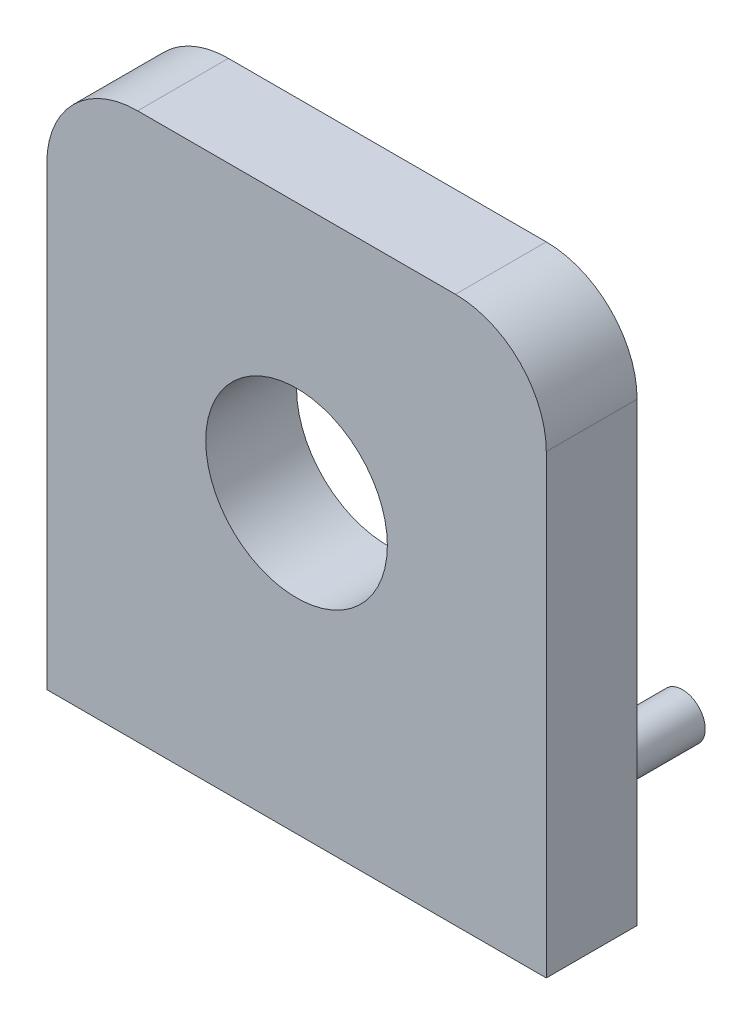
SolidWorks part; units mm, degrees
ref_plane "Front Plane" through (0, 0, 0) normal (0, 0, 1) x (1, 0, 0)
ref_plane "Top Plane" through (0, 0, 0) normal (0, 1, 0) x (1, 0, 0)
ref_plane "Right Plane" through (0, 0, 0) normal (1, 0, 0) x (0, 0, -1)
sketch "Sketch1" plane through (0, 0, 0) normal (0, 0, 1) x (1, 0, 0)
  line L0 (0, 0) -> (-5.5, 0) construction
  line L1 (0, 0) -> (5.5, 0) construction
  line L2 (0, 0) -> (0, 5.54) construction
  line L3 (0, 0) -> (0, -6.5) construction
sketch "Sketch3" plane through (0, 0, 0) normal (0, 0, 1) x (1, 0, 0)
  line L0 (5.5, -6.5) -> (-5.5, -6.5)
  line L1 (-5.5, -6.5) -> (-5.5, 5.54)
  line L2 (-5.5, 5.54) -> (5.5, 5.54)
  line L3 (5.5, 5.54) -> (5.5, -6.5)
extrude "Boss-Extrude1" add sketch "Sketch3" along normal blind 2
fillet "Fillet1" radius 2 2 edges at (-5.5, 5.54, 1) (5.5, 5.54, 1)
sketch "Sketch4" plane through (0, 0, 0) normal (0, 0, 1) x (1, 0, 0)
  circle A0 centre (0, 0) radius 2
extrude "Cut-Extrude1" cut sketch "Sketch4" along normal blind 2
sketch "Sketch5" plane through (0, 0, 0) normal (0, 0, 1) x (1, 0, 0)
  line L0 (0, 0) -> (0, 5.54) construction
  line L1 (0, 0) -> (-5.5, 0) construction
  line L2 (0, 0) -> (5.5, 0) construction
  line L3 (0, 0) -> (0, -6.5) construction
  circle A0 centre (2.5, 3) radius 0.5
  circle A1 centre (-2.5, 3) radius 0.5
  circle A2 centre (2.5, -4.493) radius 0.5
  circle A3 centre (-2.5, -4.493) radius 0.5
  dimension "D1" = 2.5
  dimension "D2" = 3
  dimension "D3" = 2.5
  dimension "D4" = 3
  dimension "D5" = 2.5
  dimension "D6" = 2.5
  dimension "D7" = 4.493
  dimension "D8" = 4.493
extrude "Boss-Extrude2" add sketch "Sketch5" against normal blind 0.5
sketch "Sketch6" plane through (0, 0, 0) normal (0, 0, -1) x (-1, 0, 0)
  line L0 (0, 0) -> (0, -6.5) construction
  line L1 (5.5, -6.5) -> (-5.5, -6.5) construction
  circle A0 centre (0, -6) radius 0.5
  circle A1 centre (2.5, -6) radius 0.5
  circle A2 centre (-2.5, -6) radius 0.5
  dimension "D1" = 0.5
  dimension "D2" = 0.5
  dimension "D3" = 0.5
  dimension "D4" = 2.5
  dimension "D5" = 2.5
extrude "Boss-Extrude3" add sketch "Sketch6" along normal blind 4
sketch "Sketch7" plane through (0, 0, 0) normal (0, 0, -1) x (-1, 0, 0)
  line L0 (-2, 0) -> (0.9, 0) construction
  line L1 (0, 0) -> (-5.5, 0) construction
  line L2 (0, 0) -> (5.5, 0) construction
  line L3 (0.9, 0) -> (0.9, 1.7861) construction
  line L4 (0.9, 0) -> (0.9, -1.7861) construction
  circle A0 centre (0, 0) radius 2 construction
